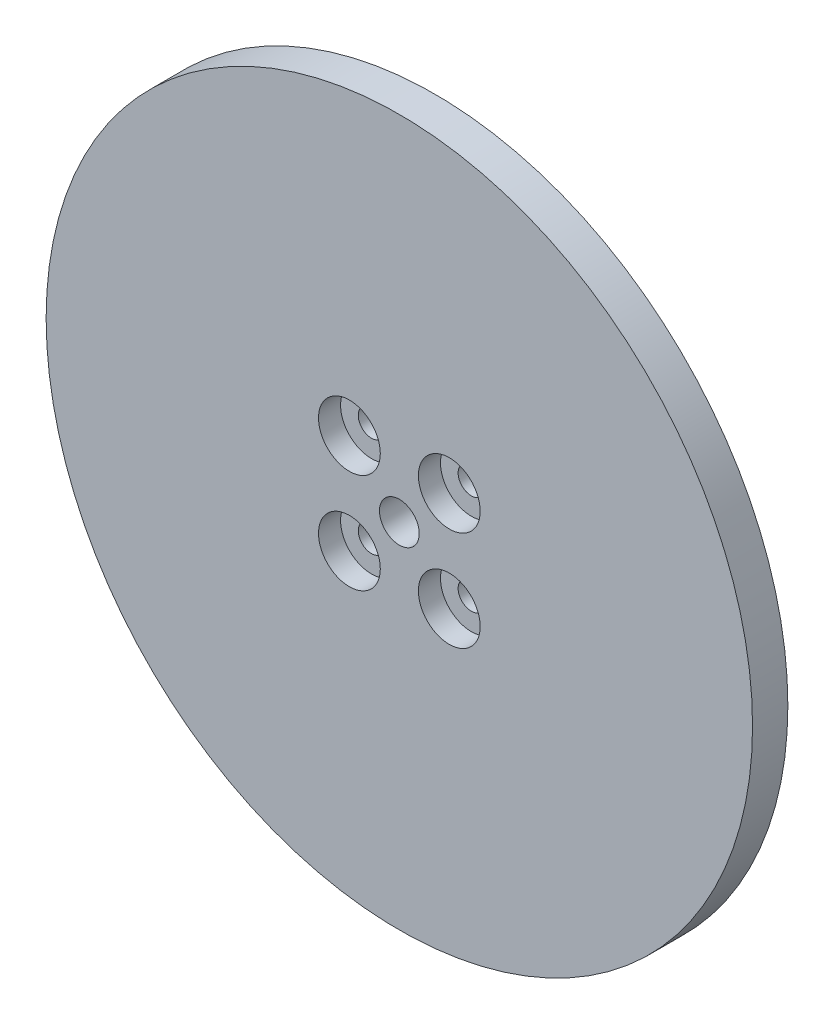
SolidWorks part; units mm, degrees
ref_plane "Front Plane" through (0, 0, 0) normal (0, 0, 1) x (1, 0, 0)
ref_plane "Top Plane" through (0, 0, 0) normal (0, 1, 0) x (1, 0, 0)
ref_plane "Right Plane" through (0, 0, 0) normal (1, 0, 0) x (0, 0, -1)
sketch "Sketch1" plane through (0, 0, 0) normal (0, 0, 1) x (1, 0, 0)
  circle A0 centre (0, 0) radius 12.5
  circle A1 centre (0, 0) radius 25
  dimension "D1" = 25
  dimension "D2" = 50
extrude "Boss-Extrude1" add sketch "Sketch1" along normal blind 2.5
sketch "Sketch2" plane through (0, 0, 2.5) normal (0, 0, 1) x (1, 0, 0)
  line L1 (-5.656, 5.6577) -> (5.656, 5.6577) construction
  line L2 (-5.656, 5.6577) -> (-5.656, -5.6577) construction
  line L3 (-5.656, -5.6577) -> (5.656, -5.6577) construction
  line L4 (5.656, 5.6577) -> (5.656, -5.6577) construction
  circle A0 centre (0, 0) radius 2.25
  circle A1 centre (-5.656, 5.6577) radius 1.5
  circle A2 centre (-5.656, -5.6577) radius 1.5
  circle A3 centre (5.656, -5.6577) radius 1.5
  circle A4 centre (5.656, 5.6577) radius 1.5
  circle A5 centre (0, 0) radius 40
  point P15 (0, -5.6577)
  point P16 (-5.656, 0)
  dimension "D1" = 4.5
  dimension "D4" = 3
  dimension "D5" = 80
  dimension "D2" = 16
  dimension "D3" = 11.3154
extrude "Boss-Extrude2" add sketch "Sketch2" along normal blind 4
sketch "Sketch3" plane through (0, 0, 6.5) normal (0, 0, 1) x (1, 0, 0)
  circle A0 centre (-5.656, 5.6577) radius 3.5
  circle A1 centre (5.656, 5.6577) radius 3.5
  circle A2 centre (5.656, -5.6577) radius 3.5
  circle A3 centre (-5.656, -5.6577) radius 3.5
  dimension "D1" = 7
extrude "Cut-Extrude1" cut sketch "Sketch3" against normal blind 2.5
